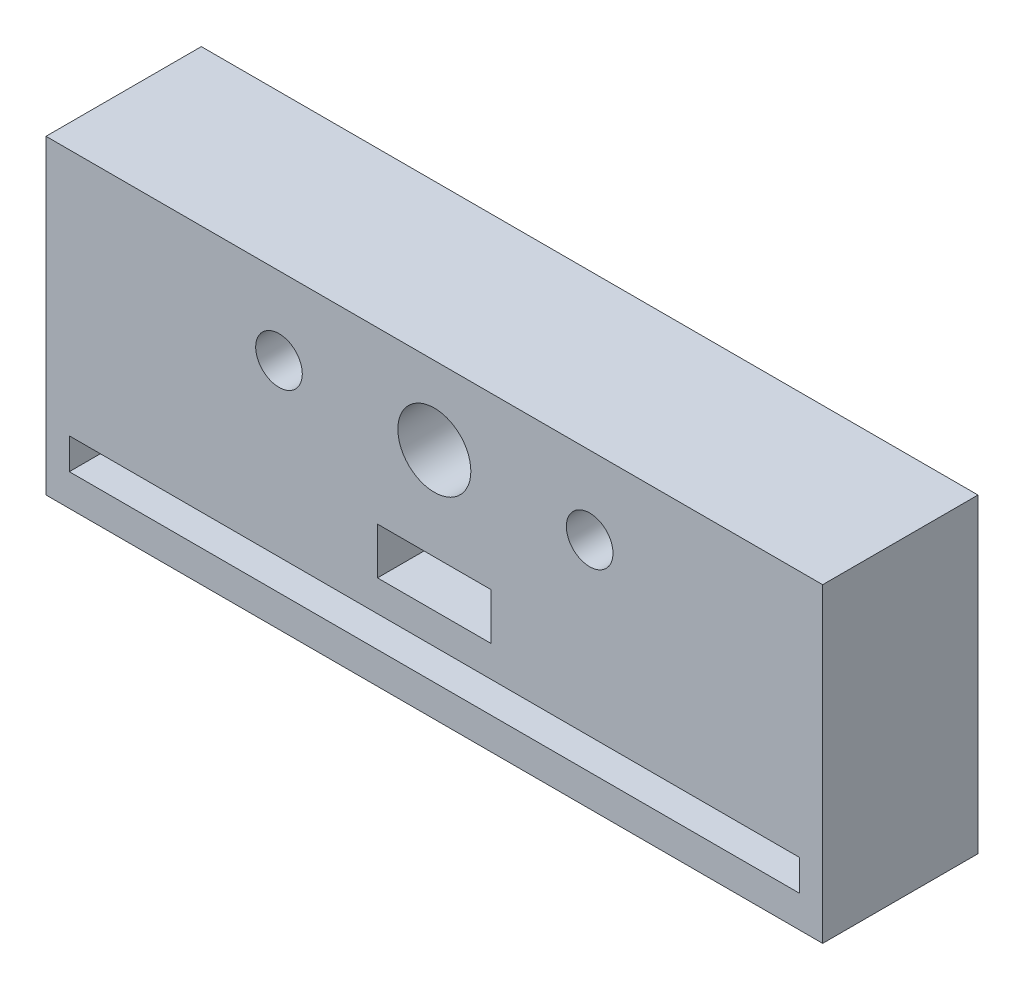
SolidWorks part; units mm, degrees
ref_plane "Front Plane" through (0, 0, 0) normal (0, 0, 1) x (1, 0, 0)
ref_plane "Top Plane" through (0, 0, 0) normal (0, 1, 0) x (1, 0, 0)
ref_plane "Right Plane" through (0, 0, 0) normal (1, 0, 0) x (0, 0, -1)
sketch "Sketch1" plane through (0, 0, 0) normal (0, 0, 1) x (1, 0, 0)
  line L1 (-3.66, 1.5) -> (3.66, 1.5)
  line L2 (-3.66, 1.5) -> (-3.66, -1.5)
  line L3 (-3.66, -1.5) -> (3.66, -1.5)
  line L4 (3.66, 1.5) -> (3.66, -1.5)
  line L5 (-3.66, 1.5) -> (3.66, -1.5) construction
  line L6 (-3.66, -1.5) -> (3.66, 1.5) construction
  line L7 (-25, -7.5493) -> (25, -7.5493)
  line L8 (-25, -7.5493) -> (-25, 12.4507)
  line L9 (-25, 12.4507) -> (25, 12.4507)
  line L10 (25, -7.5493) -> (25, 12.4507)
  line L11 (-23.5, -3.5) -> (23.5, -3.5)
  line L12 (-23.5, -3.5) -> (-23.5, -5.5)
  line L13 (-23.5, -5.5) -> (23.5, -5.5)
  line L14 (23.5, -3.5) -> (23.5, -5.5)
  circle A0 centre (-10, 7.4507) radius 1.5
  circle A1 centre (10, 7.4507) radius 1.5
  circle A2 centre (0, 7.4507) radius 2.35
  point P0 (0, 0)
  point P10 (0, 12.4507)
  point P19 (0, -3.5)
  point P20 (0, 1.5)
  dimension "D5" = 3
  dimension "D11" = 2
  dimension "D13" = 4.7
  dimension "D1" = 7.32
  dimension "D2" = 3
  dimension "D3" = 20
  dimension "D4" = 50
  dimension "D6" = 20
  dimension "D7" = 10
  dimension "D8" = 15
  dimension "D9" = 2
  dimension "D10" = 47
  dimension "D12" = 1.5
extrude "Boss-Extrude1" add sketch "Sketch1" along normal blind 10
